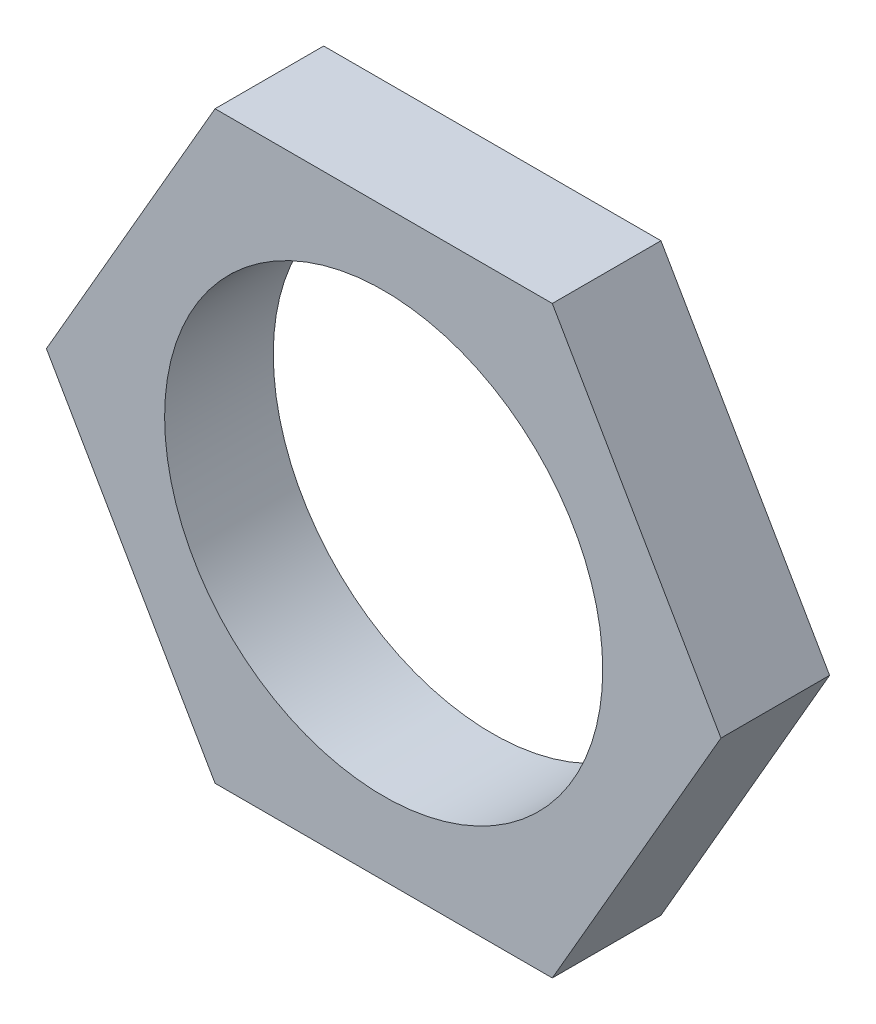
SolidWorks part; units mm, degrees
ref_plane "Front Plane" through (0, 0, 0) normal (0, 0, 1) x (1, 0, 0)
ref_plane "Top Plane" through (0, 0, 0) normal (0, 1, 0) x (1, 0, 0)
ref_plane "Right Plane" through (0, 0, 0) normal (1, 0, 0) x (0, 0, -1)
sketch "Sketch1" plane through (0, 0, 0) normal (0, 0, 1) x (1, 0, 0)
  line L0 (0, 0) -> (-109.7498, 0) construction
  line L1 (-54.8749, 0) -> (-54.8749, 2.9869) construction
  line L2 (-58.5411, 2.9869) -> (-51.2087, 2.9869)
  line L3 (-51.2087, 2.9869) -> (-47.5426, -3.3631)
  line L4 (-47.5426, -3.3631) -> (-51.2087, -9.7131)
  line L5 (-51.2087, -9.7131) -> (-58.5411, -9.7131)
  line L6 (-58.5411, -9.7131) -> (-62.2073, -3.3631)
  line L7 (-62.2073, -3.3631) -> (-58.5411, 2.9869)
  point P19 (-54.8749, -3.3631)
  dimension "D1" = 12.7
  dimension "D2" = 6
sketch "Sketch2" plane through (0, 0, 0) normal (0, 0, 1) x (1, 0, 0)
  line L0 (-58.5411, -9.7131) -> (-62.2073, -3.3631) construction
  line L1 (-62.2073, -3.3631) -> (-58.5411, 2.9869) construction
  line L2 (-58.5411, 2.9869) -> (-51.2087, 2.9869) construction
  line L3 (-51.2087, 2.9869) -> (-47.5426, -3.3631) construction
  line L4 (-47.5426, -3.3631) -> (-51.2087, -9.7131) construction
  line L5 (-51.2087, -9.7131) -> (-58.5411, -9.7131) construction
  line L6 (-58.5411, -9.7131) -> (-62.2073, -3.3631)
  line L7 (-62.2073, -3.3631) -> (-58.5411, 2.9869)
  line L8 (-58.5411, 2.9869) -> (-51.2087, 2.9869)
  line L9 (-51.2087, 2.9869) -> (-47.5426, -3.3631)
  line L10 (-47.5426, -3.3631) -> (-51.2087, -9.7131)
  line L11 (-51.2087, -9.7131) -> (-58.5411, -9.7131)
extrude "Boss-Extrude1" add sketch "Sketch2" along normal blind 2.3622
sketch "Sketch3" plane through (0, 0, 2.3622) normal (0, 0, 1) x (1, 0, 0)
  line L0 (-54.8749, 2.9869) -> (-54.8749, -9.7131) construction
  line L1 (-51.2087, 2.9869) -> (-58.5411, 2.9869) construction
  line L2 (-58.5411, -9.7131) -> (-51.2087, -9.7131) construction
  circle A0 centre (-54.8749, -3.3631) radius 4.7625
  point P6 (-54.8749, -3.3631)
  dimension "D1" = 9.525
extrude "Cut-Extrude1" cut sketch "Sketch3" against normal through all
